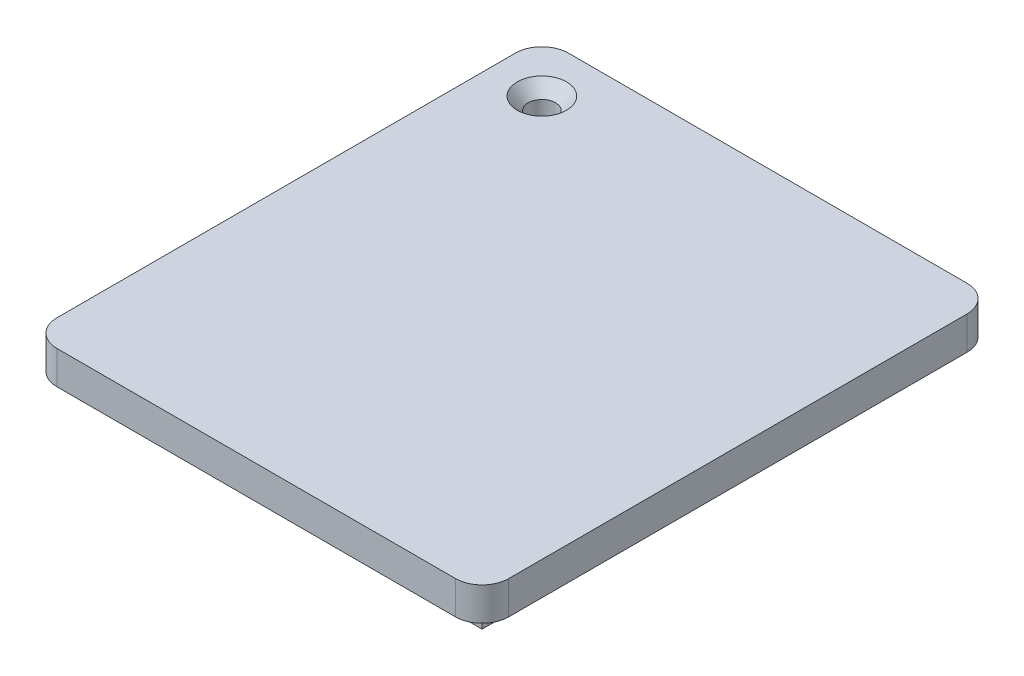
SolidWorks part; units mm, degrees
ref_plane "Front Plane" through (0, 0, 0) normal (0, 0, 1) x (1, 0, 0)
ref_plane "Top Plane" through (0, 0, 0) normal (0, 1, 0) x (1, 0, 0)
ref_plane "Right Plane" through (0, 0, 0) normal (1, 0, 0) x (0, 0, -1)
sketch "Sketch1" plane through (0, 0, 0) normal (0, 0, 1) x (1, 0, 0)
  line L0 (-24.05, 2) -> (-24.05, 0.8637) construction
  line L1 (-24.05, 2) -> (9.95, 2)
  line L2 (-24.05, 2) -> (-24.05, 4.5)
  line L3 (-24.05, 4.5) -> (9.95, 4.5)
  line L4 (9.95, 4.5) -> (9.95, 2)
  line L6 (9.95, 1.1642) -> (9.95, 2) construction
  dimension "D1" = 2.5
  dimension "D2" = 34
extrude "Extrude1" add sketch "Sketch1" against normal blind 38.5
fillet "Fillet1" radius 2 4 edges at (-24.05, 3.25, 0) (-24.05, 3.25, -38.5) (9.95, 3.25, -38.5) (9.95, 3.25, 0)
sketch "Sketch2" plane through (0, 2, 0) normal (0, -1, 0) x (1, 0, 0)
  line L0 (-24.05, -36.5) -> (-24.05, -2) construction
  line L1 (-22.85, -1.2) -> (8.75, -1.2)
  line L2 (-22.85, -1.2) -> (-22.85, -37.3)
  line L3 (-22.85, -37.3) -> (8.75, -37.3)
  line L4 (8.75, -1.2) -> (8.75, -37.3)
  line L5 (-22.05, 0) -> (7.95, 0) construction
  line L7 (-22.05, -38.5) -> (7.95, -38.5) construction
  dimension "D1" = 1.2
  dimension "D2" = 1.2
  dimension "D4" = 1.2
extrude "Extrude2" add sketch "Sketch2" along normal blind 1
hole_wizard "CSK for #1 Flat Head Machine Screw1" positions "3DSketch1" profile "Sketch3" countersink size "#1" standard "Ansi Inch" end condition through all
sketch3d "3DSketch1"
  line L6 (7.95, 4.5, -38.5) -> (-22.05, 4.5, -38.5) construction
  line L7 (-24.05, 4.5, -36.5) -> (-24.05, 4.5, -2) construction
  point P15 (-20.25, 4.5, -34.7)
  dimension "D1" = 3.8
  dimension "D2" = 3.8
sketch "Sketch3" plane through (-20.25, 4.5, -34.7) normal (1, 0, 0) x (0, 0, 1)
  line L0 (0, 0) -> (0, 3.5)
  line L1 (0, 3.5) -> (1.0287, 3.5)
  line L2 (1.0287, 3.5) -> (1.0287, 0.9496)
  line L3 (1.0287, 0.9496) -> (1.8542, 0)
  line L5 (1.8542, 0) -> (0, 0)
  line L6 (-1.0287, 0.9496) -> (-1.8542, 0) construction
  line L11 (0, -6.35) -> (0, 107.95) construction
  dimension "Thru Hole Dia." = 2.0574
  dimension "Thru Hole Depth" = 3.5
  dimension "Near C'Sink Dia." = 3.7084
  dimension "Near C'Sink Angle" = 82
